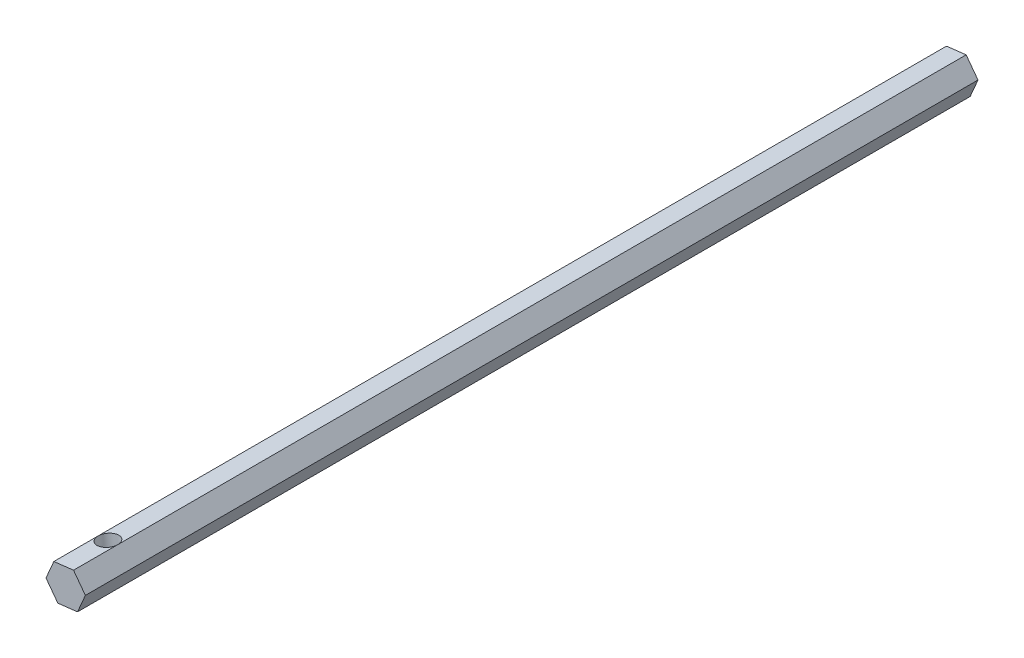
SolidWorks part; units mm, degrees
ref_plane "Front Plane" through (0, 0, 0) normal (0, 0, 1) x (1, 0, 0)
ref_plane "Top Plane" through (0, 0, 0) normal (0, 1, 0) x (1, 0, 0)
ref_plane "Right Plane" through (0, 0, 0) normal (1, 0, 0) x (0, 0, -1)
sketch "Sketch1" plane through (0, 0, 0) normal (0, 0, 1) x (1, 0, 0)
  line L1 (5.8022, 13.4694) -> (-8.7637, 11.7596)
  line L2 (-8.7637, 11.7596) -> (-14.5659, -1.7098)
  line L3 (-14.5659, -1.7098) -> (-5.8022, -13.4694)
  line L4 (-5.8022, -13.4694) -> (8.7637, -11.7596)
  line L5 (8.7637, -11.7596) -> (14.5659, 1.7098)
  line L6 (14.5659, 1.7098) -> (5.8022, 13.4694)
  circle A0 centre (0, 0) radius 12.7011 construction
extrude "Boss-Extrude1" add sketch "Sketch1" along normal blind 660.4
sketch "Sketch2" plane through (-1.4808, 12.6145, 0) normal (-0.1166, 0.9932, 0) x (0.9932, 0.1166, 0)
  line L0 (0, -660.4) -> (0, -635)
  line L1 (7.333, -660.4) -> (-7.333, -660.4) construction
  line L2 (0, -635) -> (0, -627.667)
  ellipse E0 centre (0, -627.667) end of major axis (-7.333, -627.667) minor radius 7.2764
extrude "Cut-Extrude1" cut sketch "Sketch2" against normal blind 33.02 contours E0
